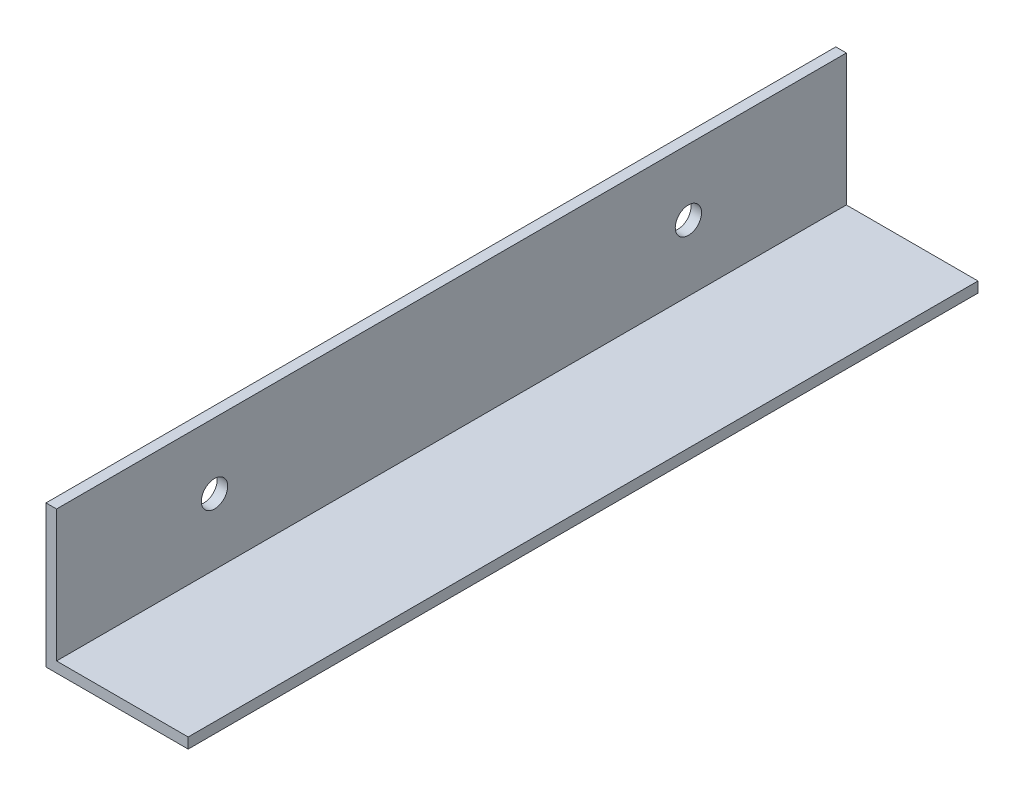
SolidWorks part; units mm, degrees
ref_plane "Front Plane" through (0, 0, 0) normal (0, 0, 1) x (1, 0, 0)
ref_plane "Top Plane" through (0, 0, 0) normal (0, 1, 0) x (1, 0, 0)
ref_plane "Right Plane" through (0, 0, 0) normal (1, 0, 0) x (0, 0, -1)
sketch "Sketch1" plane through (0, 0, 0) normal (0, 0, 1) x (1, 0, 0)
  line L0 (0, 0) -> (25, 0)
  line L1 (0, 0) -> (0, 25)
  line L2 (-2, -2) -> (25, -2)
  line L3 (-2, -2) -> (-2, 25)
  line L4 (-2, 25) -> (0, 25)
  line L5 (25, 0) -> (25, -2)
  dimension "D1" = 25
  dimension "D2" = 2
extrude "Boss-Extrude1" add sketch "Sketch1" along normal blind 150
sketch "Sketch2" plane through (0, 0, 0) normal (1, 0, 0) x (0, 0, -1)
  line L0 (-150, 12.5) -> (0, 12.5) construction
  line L1 (-150, 0) -> (-150, 25) construction
  line L2 (0, 0) -> (0, 25) construction
  circle A0 centre (-120, 12.5) radius 2.5
  circle A1 centre (-30, 12.5) radius 2.5
  point P10 (-75, 12.5)
  dimension "D1" = 5
  dimension "D2" = 5
  dimension "D3" = 45
  dimension "D4" = 45
extrude "Cut-Extrude1" cut sketch "Sketch2" against normal through all both and the other way through all
